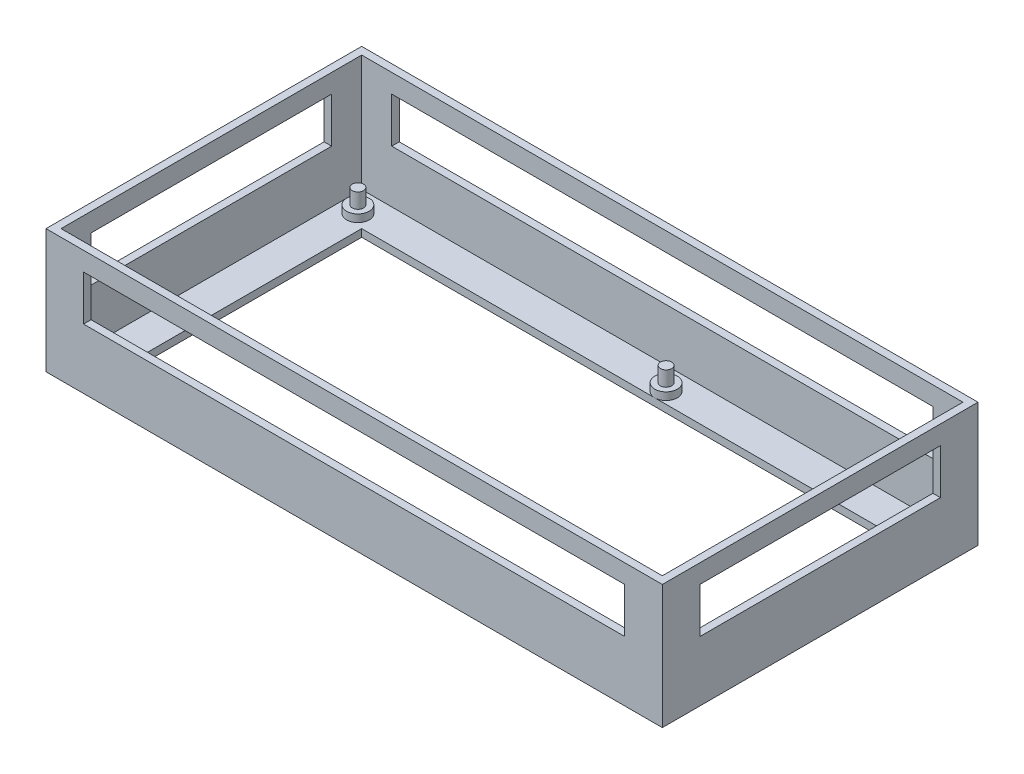
SolidWorks part; units mm, degrees
ref_plane "Front Plane" through (0, 0, 0) normal (0, 0, 1) x (1, 0, 0)
ref_plane "Top Plane" through (0, 0, 0) normal (0, 1, 0) x (1, 0, 0)
ref_plane "Right Plane" through (0, 0, 0) normal (1, 0, 0) x (0, 0, -1)
sketch "Sketch1" plane through (0, 0, 0) normal (0, 1, 0) x (1, 0, 0)
  line L1 (0, 0) -> (164, 0)
  line L2 (0, 0) -> (0, 84)
  line L3 (0, 84) -> (164, 84)
  line L4 (164, 0) -> (164, 84)
  dimension "D1" = 164
  dimension "D2" = 84
extrude "Boss-Extrude1" add sketch "Sketch1" along normal blind 33
shell "Shell1" thickness 2
sketch "Sketch3" plane through (0, 2, 0) normal (0, 1, 0) x (1, 0, 0)
  line L8 (11, 73) -> (11, 11)
  line L9 (11, 11) -> (153, 11)
  line L10 (153, 11) -> (153, 73)
  line L11 (153, 73) -> (11, 73)
  line L12 (11, 73) -> (11, 11)
  line L13 (11, 11) -> (153, 11)
  line L14 (153, 11) -> (153, 73)
  line L15 (153, 73) -> (11, 73)
  dimension "D1" = 9
extrude "Cut-Extrude1" cut sketch "Sketch3" against normal up to surface (2 mm away) up to face at (82, 0, -42)
sketch "Sketch4" plane through (0, 2, 0) normal (0, 1, 0) x (1, 0, 0)
  line L0 (162, 2) -> (162, 82) construction
  line L1 (162, 82) -> (2, 82) construction
  line L3 (2, 2) -> (162, 2) construction
  circle A0 centre (157, 76) radius 3
  circle A1 centre (89, 76) radius 3
  circle A2 centre (89, 8) radius 3
  circle A3 centre (157, 8) radius 3
  point P8 (0, 0)
  dimension "D1" = 6
  dimension "D2" = 68
  dimension "D3" = 68
  dimension "D4" = 68
  dimension "D5" = 68
  dimension "D6" = 5
  dimension "D7" = 6
  dimension "D8" = 6
  dimension "D9" = 6
extrude "Boss-Extrude2" add sketch "Sketch4" along normal blind 2 contours A0 | A1 | A2 | A3
sketch "Sketch5" plane through (0, 4, 0) normal (0, 1, 0) x (1, 0, 0)
  circle A0 centre (89, 76) radius 1.5
  circle A1 centre (157, 76) radius 1.5
  circle A2 centre (89, 8) radius 1.5
  circle A3 centre (157, 8) radius 1.5
  dimension "D1" = 3
extrude "Boss-Extrude3" add sketch "Sketch5" along normal blind 4
sketch "Sketch6" plane through (0, 2, 0) normal (0, 1, 0) x (1, 0, 0)
  line L0 (2, 82) -> (2, 2) construction
  line L1 (0, 0) -> (164, 0) construction
  line L3 (164, 84) -> (0, 84) construction
  circle A0 centre (7, 76) radius 3
  circle A3 centre (7, 8) radius 3
  circle A4 centre (63, 8) radius 3
  dimension "D1" = 6
  dimension "D2" = 68
  dimension "D3" = 56
  dimension "D4" = 5
  dimension "D5" = 8
  dimension "D6" = 8
  dimension "D7" = 8
extrude "Boss-Extrude4" add sketch "Sketch6" along normal blind 2
sketch "Sketch7" plane through (0, 4, 0) normal (0, 1, 0) x (1, 0, 0)
  circle A0 centre (7, 76) radius 1.5
  circle A1 centre (7, 8) radius 1.5
  circle A2 centre (63, 8) radius 1.5
  dimension "D1" = 3
extrude "Boss-Extrude5" add sketch "Sketch7" along normal blind 4
sketch "Sketch8" plane through (0, 0, 0) normal (-1, 0, 0) x (0, 0, 1)
  line L0 (-84, 16.5) -> (0, 16.5) construction
  line L1 (-84, 33) -> (-84, 0) construction
  line L2 (0, 33) -> (0, 0) construction
  line L3 (-42, 33) -> (-42, 0) construction
  line L4 (-84, 33) -> (0, 33) construction
  line L5 (-84, 0) -> (0, 0) construction
  line L7 (-74, 28) -> (-10, 28)
  line L8 (-74, 28) -> (-74, 16)
  line L9 (-74, 16) -> (-10, 16)
  line L10 (-10, 28) -> (-10, 16)
  dimension "D1" = 10
  dimension "D2" = 10
  dimension "D3" = 5
  dimension "D4" = 16
extrude "Cut-Extrude2" cut sketch "Sketch8" against normal through all
sketch "Sketch9" plane through (0, 0, 0) normal (0, 0, 1) x (1, 0, 0)
  line L0 (0, 33) -> (164, 33) construction
  line L1 (10, 28) -> (154, 28)
  line L2 (10, 28) -> (10, 16)
  line L3 (10, 16) -> (154, 16)
  line L4 (154, 28) -> (154, 16)
  line L5 (0, 33) -> (0, 0) construction
  line L6 (164, 33) -> (164, 0) construction
  line L7 (0, 0) -> (164, 0) construction
  dimension "D1" = 5
  dimension "D2" = 10
  dimension "D3" = 10
  dimension "D4" = 16
extrude "Cut-Extrude3" cut sketch "Sketch9" against normal through all
sketch "Sketch10" plane through (0, 33, 0) normal (0, 1, 0) x (1, 0, 0)
  line L1 (0, 84) -> (164, 84)
  line L2 (0, 84) -> (0, 0)
  line L3 (0, 0) -> (164, 0)
  line L4 (164, 84) -> (164, 0)
